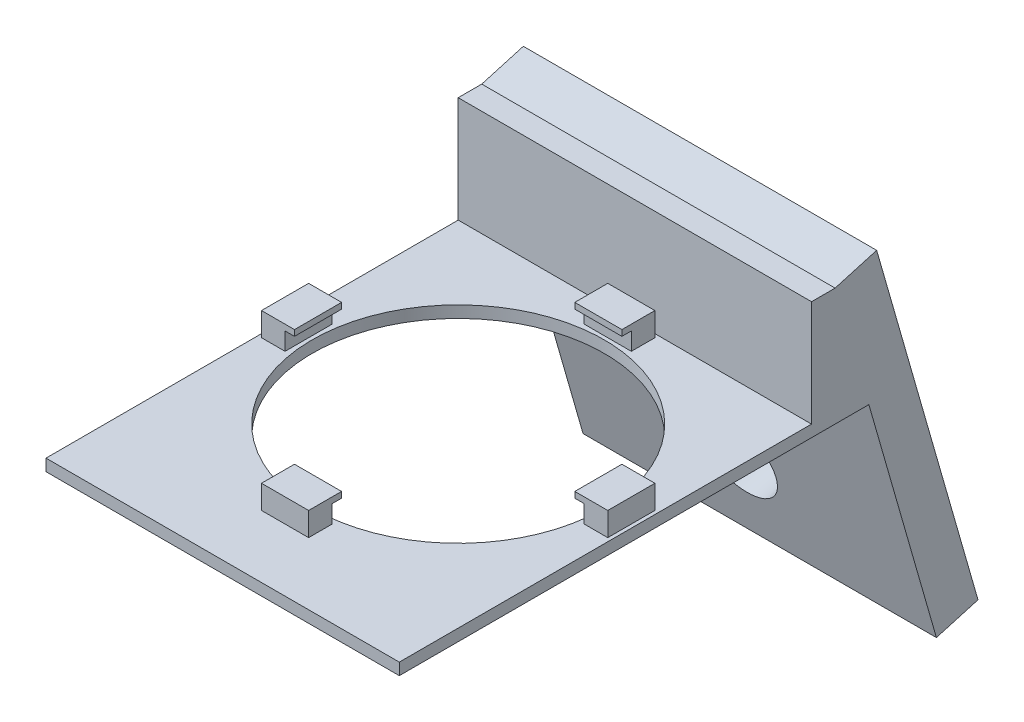
SolidWorks part; units mm, degrees
ref_plane "Front Plane" through (0, 0, 0) normal (0, 0, 1) x (1, 0, 0)
ref_plane "Top Plane" through (0, 0, 0) normal (0, 1, 0) x (1, 0, 0)
ref_plane "Right Plane" through (0, 0, 0) normal (1, 0, 0) x (0, 0, -1)
sketch "Sketch1" plane through (0, 0, 0) normal (0, 1, 0) x (1, 0, 0)
  line L1 (-15, -15) -> (15, -15)
  line L2 (-15, -15) -> (-15, 15)
  line L3 (-15, 15) -> (15, 15)
  line L4 (15, -15) -> (15, 15)
  line L5 (-15, -15) -> (15, 15) construction
  line L6 (-15, 15) -> (15, -15) construction
  point P0 (0, 0)
  dimension "D1" = 30
  dimension "D2" = 30
extrude "Boss-Extrude1" add sketch "Sketch1" along normal blind 1
sketch "Sketch2" plane through (0, 1, 0) normal (0, 1, 0) x (1, 0, 0)
  circle A0 centre (0, 0) radius 12.4
  dimension "D1" = 24.8
extrude "Cut-Extrude1" cut sketch "Sketch2" against normal through all
sketch "Sketch4" plane through (0, 1, 0) normal (0, 1, 0) x (1, 0, 0)
  line L0 (15, 0) -> (12.4, 0)
  line L1 (15, -15) -> (15, 15) construction
  line L2 (0, 15) -> (0, -15)
  line L3 (14.7, 2) -> (12.7, 2)
  line L4 (14.7, 2) -> (14.7, -2)
  line L5 (14.7, -2) -> (12.7, -2)
  line L6 (12.7, 2) -> (12.7, -2)
  line L7 (14.7, 2) -> (12.7, -2) construction
  line L8 (14.7, -2) -> (12.7, 2) construction
  line L9 (15, 15) -> (-15, 15) construction
  line L10 (-15, -15) -> (15, -15) construction
  line L11 (-12.4, 0) -> (0, 0)
  line L12 (-14.7, -2) -> (-12.7, -2)
  line L13 (-12.7, 2) -> (-12.7, -2)
  line L14 (-14.7, 2) -> (-12.7, 2)
  line L15 (-14.7, 2) -> (-14.7, -2)
  line L16 (2, 12.7) -> (-2, 12.7)
  line L17 (2, 14.7) -> (2, 12.7)
  line L18 (2, 14.7) -> (-2, 14.7)
  line L19 (-2, 14.7) -> (-2, 12.7)
  line L20 (12.7, -2) -> (12.7, 2)
  line L21 (14.7, -2) -> (12.7, -2)
  line L22 (14.7, -2) -> (14.7, 2)
  line L23 (14.7, 2) -> (12.7, 2)
  line L24 (-2, -12.7) -> (2, -12.7)
  line L25 (-2, -14.7) -> (-2, -12.7)
  line L26 (-2, -14.7) -> (2, -14.7)
  line L27 (2, -14.7) -> (2, -12.7)
  circle A0 centre (0, 0) radius 12.4 construction
  point P7 (13.7, 0)
  point P41 (0, 0)
  dimension "D1" = 0.3
  dimension "D2" = 4
  dimension "D3" = 4
extrude "Boss-Extrude2" add sketch "Sketch4" along normal blind 2 contours L17 L16 L19 L18 | L4 L5 L6 L3 | L27 L24 L25 L26 | L13 L12 L15 L14
sketch "Sketch5" plane through (12.7, 0, 0) normal (-1, 0, 0) x (0, 0, 1)
  line L0 (2, 3) -> (2, 1) construction
  line L1 (-2, 3) -> (2, 3)
  line L2 (-2, 3) -> (-2, 2.5)
  line L3 (-2, 2.5) -> (2, 2.5)
  line L4 (2, 3) -> (2, 2.5)
  dimension "D1" = 0.5
extrude "Boss-Extrude3" add sketch "Sketch5" along normal blind 0.8
sketch "Sketch6" plane through (0, 0, 12.7) normal (0, 0, -1) x (-1, 0, 0)
  line L0 (2, 3) -> (2, 1) construction
  line L1 (-2, 3) -> (2, 3)
  line L2 (-2, 3) -> (-2, 2.5)
  line L3 (-2, 2.5) -> (2, 2.5)
  line L4 (2, 3) -> (2, 2.5)
  dimension "D1" = 0.5
extrude "Boss-Extrude4" add sketch "Sketch6" along normal blind 0.8
sketch "Sketch7" plane through (-12.7, 0, 0) normal (1, 0, 0) x (0, 0, -1)
  line L0 (2, 3) -> (2, 1) construction
  line L1 (-2, 3) -> (2, 3)
  line L2 (-2, 3) -> (-2, 2.5)
  line L3 (-2, 2.5) -> (2, 2.5)
  line L4 (2, 3) -> (2, 2.5)
  dimension "D1" = 0.5
extrude "Boss-Extrude5" add sketch "Sketch7" along normal blind 0.8
sketch "Sketch8" plane through (0, 0, -12.7) normal (0, 0, 1) x (1, 0, 0)
  line L0 (2, 3) -> (2, 1) construction
  line L1 (-2, 3) -> (2, 3)
  line L2 (-2, 3) -> (-2, 2.5)
  line L3 (-2, 2.5) -> (2, 2.5)
  line L4 (2, 3) -> (2, 2.5)
  dimension "D1" = 0.5
extrude "Boss-Extrude6" add sketch "Sketch8" along normal blind 0.8
sketch "Sketch11" plane through (0, 0, 0) normal (0, -1, 0) x (1, 0, 0)
  line L0 (-15, -15) -> (-15, -17)
  line L1 (-15, -15) -> (23.9307, -15)
  line L2 (-15, -17) -> (23.9307, -17)
  line L3 (23.9307, -15) -> (23.9307, -17)
  dimension "D1" = 2
extrude "Boss-Extrude9" add sketch "Sketch11" against normal blind 10
sketch "Sketch12" plane through (-15, 0, 0) normal (-1, 0, 0) x (0, 0, 1)
  line L0 (-17, 10) -> (-25.6024, -20)
  line L1 (-12.4, 0) -> (12.4, 0) construction
  line L2 (-25.6024, -20) -> (-30.3653, -18.6343)
  line L3 (-30.3653, -18.6343) -> (-21.7629, 11.3657)
  line L4 (-21.7629, 11.3657) -> (-17, 10)
  dimension "D1" = 74
  dimension "D2" = 90
  dimension "D3" = 30
  dimension "D4" = 30
extrude "Boss-Extrude10" add sketch "Sketch12" against normal blind 30 separate body
sketch "Sketch13" plane through (-15, 0, 0) normal (-1, 0, 0) x (0, 0, 1)
  line L0 (-17, 0) -> (-25.022, 0)
  line L1 (-21.7629, 11.3657) -> (-30.3653, -18.6343) construction
  line L2 (-25.022, 0) -> (-21.7629, 11.3657)
  line L3 (-21.7629, 11.3657) -> (-17, 10)
  line L4 (-17, 10) -> (-17, 0)
extrude "Boss-Extrude11" add sketch "Sketch13" against normal blind 30
sketch "Sketch14" plane through (0, 0, -17) normal (0, 0, -1) x (-1, 0, 0)
  line L0 (-23.9307, 10) -> (-15, 10)
  line L1 (-23.9307, 10) -> (-23.9307, 0)
  line L2 (-23.9307, 0) -> (-15, 0)
  line L3 (-15, 0) -> (-15, 10)
extrude "Cut-Extrude2" cut sketch "Sketch14" against normal through all both and the other way through all
sketch "Sketch15" plane through (0, 0, 15) normal (0, 0, 1) x (1, 0, 0)
  line L0 (15, 1) -> (15, 0)
  line L1 (15, 1) -> (-14.9963, 1)
  line L2 (15, 0) -> (-14.9963, 0)
  line L3 (-14.9963, 1) -> (-14.9963, 0)
extrude "Boss-Extrude12" add sketch "Sketch15" along normal blind 5
sketch "Sketch20" plane through (0, -25.2641, -7.2444) normal (0, -0.9613, -0.2756) x (1, 0, 0)
  line L0 (-15, -19.0978) -> (15, -19.0978)
  line L1 (-15, -19.0978) -> (-15, -22.7711)
  line L2 (15, -19.0978) -> (15, -22.7711)
  line L3 (-15, -22.7711) -> (15, -22.7711)
extrude "Boss-Extrude16" add sketch "Sketch20" against normal blind 90
sketch "Sketch21" plane through (15, 0, 0) normal (1, 0, 0) x (0, 0, -1)
  line L0 (21.7629, 11.3657) -> (20.5309, 11.0125)
  line L1 (20.5309, 11.0125) -> (29.1333, -18.9875)
  line L2 (30.3653, -18.6343) -> (25.6024, -20) construction
  line L3 (29.1333, -18.9875) -> (30.3653, -18.6343)
  line L4 (30.3653, -18.6343) -> (21.7629, 11.3657)
extrude "Cut-Extrude3" cut sketch "Sketch21" against normal through all
sketch "Sketch23" plane through (0, 6.2766, -21.889) normal (0, 0.2756, -0.9613) x (-1, 0, 0)
  line L0 (-15, 63.7178) -> (15, 63.7178)
  line L1 (-15, 63.7178) -> (-15, 8.1481)
  line L2 (15, 63.7178) -> (15, 8.1481)
  line L3 (-15, 8.1481) -> (15, 8.1481)
extrude "Cut-Extrude5" cut sketch "Sketch23" against normal blind 10
sketch "Sketch24" plane through (0, 7.8324, 2.2459) normal (0, 0.9613, 0.2756) x (1, 0, 0)
  line L1 (15, 19.0978) -> (-15, 19.0978)
  line L2 (15, 19.0978) -> (15, 22.7711)
  line L3 (15, 22.7711) -> (-15, 22.7711)
  line L4 (-15, 19.0978) -> (-15, 22.7711)
extrude "Boss-Extrude17" add sketch "Sketch24" along normal blind 76.2
sketch "Sketch25" plane through (0, 81.0806, 23.2495) normal (0, 0.9613, 0.2756) x (1, 0, 0)
  line L1 (-15, 19.0978) -> (15, 19.0978)
  line L2 (-15, 19.0978) -> (-15, 22.7711)
  line L3 (-15, 22.7711) -> (15, 22.7711)
  line L4 (15, 19.0978) -> (15, 22.7711)
extrude "Cut-Extrude6" cut sketch "Sketch25" against normal blind 25.4
sketch "Sketch26" plane through (0, 56.6645, 16.2483) normal (0, 0.9613, 0.2756) x (1, 0, 0)
  line L1 (-15, 19.0978) -> (15, 19.0978)
  line L2 (-15, 19.0978) -> (-15, 22.7711)
  line L3 (-15, 22.7711) -> (15, 22.7711)
  line L4 (15, 19.0978) -> (15, 22.7711)
extrude "Boss-Extrude18" add sketch "Sketch26" along normal blind 17.8
sketch "Sketch27" plane through (0, 5.2641, -18.358) normal (0, -0.2756, 0.9613) x (1, 0, 0)
  line L1 (-15, 4.9268) -> (15, 4.9268)
  line L2 (-15, 4.9268) -> (-15, 76.7481)
  line L3 (-15, 76.7481) -> (15, 76.7481)
  line L4 (15, 4.9268) -> (15, 76.7481)
extrude "Cut-Extrude7" cut sketch "Sketch27" against normal blind 10
sketch "Sketch28" plane through (0, 5.2641, -18.358) normal (0, -0.2756, 0.9613) x (1, 0, 0)
  circle A0 centre (0, -19.05) radius 3.375
  dimension "D1" = 6.75
extrude "Cut-Extrude8" cut sketch "Sketch28" against normal blind 10
